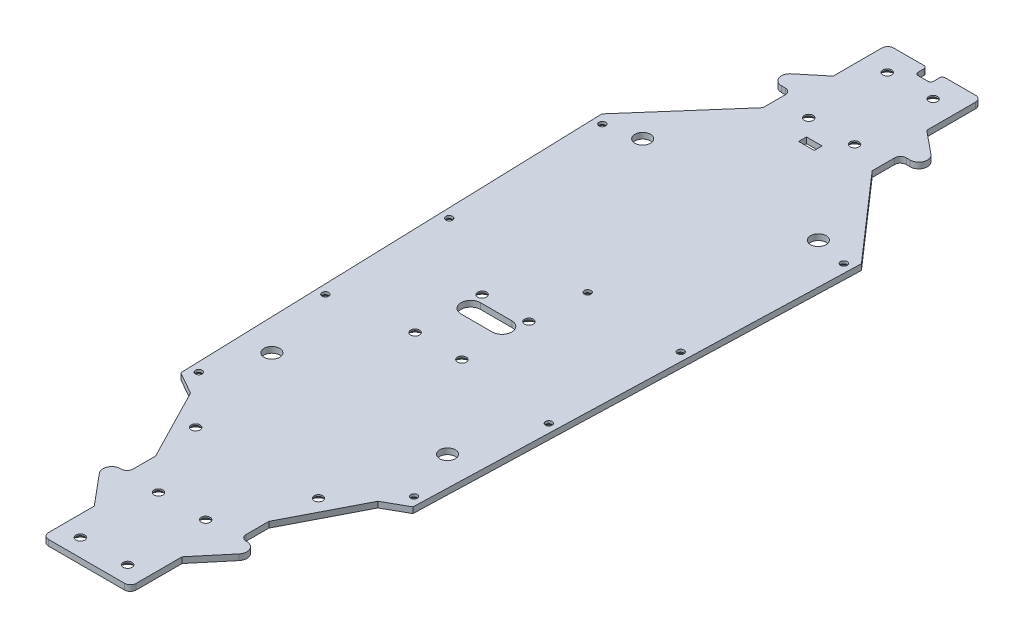
SolidWorks part; units mm, degrees
material "1060-H12"
ref_plane "Plano frontal" through (0, 0, 0) normal (0, 0, 1) x (1, 0, 0)
ref_plane "Plano superior" through (0, 0, 0) normal (0, 1, 0) x (1, 0, 0)
ref_plane "Plano direito" through (0, 0, 0) normal (1, 0, 0) x (0, 0, -1)
sketch "Esboço1" plane through (0, 0, 0) normal (0, 1, 0) x (1, 0, 0)
  line L0 (0, -26.4872) -> (0, 31.5227) construction
  line L1 (-2.5, 209.375) -> (2.5, 209.375)
  line L2 (4, 210.875) -> (4, 213.875)
  line L3 (5.5, 215.375) -> (21, 215.375)
  line L4 (24, 212.375) -> (24, 187.375)
  line L5 (24, 187.375) -> (35.8087, 177.675)
  line L6 (33.0159, 169.875) -> (31, 169.875)
  line L7 (28, 166.875) -> (28, 155.375)
  line L8 (-66.5, 111.375) -> (-28, 155.375)
  line L9 (66.5, 111.375) -> (59.5, -111.375)
  line L10 (59.5, -111.375) -> (48, -117.875)
  line L11 (48, -117.875) -> (29, -154.7701)
  line L12 (29, -154.7701) -> (29, -166.3701)
  line L13 (35.824, -176.7566) -> (22.5, -192.692)
  line L14 (32, -169.3701) -> (32.3717, -169.3701)
  line L15 (22.5, -192.692) -> (22.5, -216.192)
  line L16 (66.5, 111.375) -> (28, 155.375)
  line L17 (19.5, -219.192) -> (-19.5, -219.192)
  line L18 (-22.5, -192.692) -> (-22.5, -216.192)
  line L19 (-32, -169.3701) -> (-32.3717, -169.3701)
  line L20 (-35.824, -176.7566) -> (-22.5, -192.692)
  line L21 (-29, -154.7701) -> (-29, -166.3701)
  line L22 (-48, -117.875) -> (-29, -154.7701)
  line L23 (-59.5, -111.375) -> (-48, -117.875)
  line L24 (-66.5, 111.375) -> (-59.5, -111.375)
  line L25 (-63, 0) -> (0, 0) construction
  line L27 (-28, 166.875) -> (-28, 155.375)
  line L28 (-33.0159, 169.875) -> (-31, 169.875)
  line L29 (-24, 187.375) -> (-35.8087, 177.675)
  line L30 (-24, 212.375) -> (-24, 187.375)
  line L31 (-5.5, 215.375) -> (-21, 215.375)
  line L32 (-4, 210.875) -> (-4, 213.875)
  arc A0 (-5.5, 215.375) -> (-4, 213.875) centre (-5.5, 213.875) cw
  arc A1 (-4, 210.875) -> (-2.5, 209.375) centre (-2.5, 210.875) ccw
  arc A2 (4, 210.875) -> (2.5, 209.375) centre (2.5, 210.875) cw
  arc A3 (5.5, 215.375) -> (4, 213.875) centre (5.5, 213.875) ccw
  arc A4 (22.5, -216.192) -> (19.5, -219.192) centre (19.5, -216.192) cw
  arc A5 (24, 212.375) -> (21, 215.375) centre (21, 212.375) ccw
  arc A6 (-32, -169.3701) -> (-29, -166.3701) centre (-32, -166.3701) ccw
  arc A7 (-32.3717, -169.3701) -> (-35.824, -176.7566) centre (-32.3717, -173.8701) ccw
  arc A8 (-31, 169.875) -> (-28, 166.875) centre (-31, 166.875) cw
  arc A9 (-35.8087, 177.675) -> (-33.0159, 169.875) centre (-33.0159, 174.275) ccw
  arc A10 (-24, 212.375) -> (-21, 215.375) centre (-21, 212.375) cw
  arc A11 (-22.5, -216.192) -> (-19.5, -219.192) centre (-19.5, -216.192) ccw
  arc A12 (35.8087, 177.675) -> (33.0159, 169.875) centre (33.0159, 174.275) cw
  arc A13 (31, 169.875) -> (28, 166.875) centre (31, 166.875) ccw
  arc A14 (32.3717, -169.3701) -> (35.824, -176.7566) centre (32.3717, -173.8701) cw
  arc A15 (32, -169.3701) -> (29, -166.3701) centre (32, -166.3701) cw
  point P4 (22.5, -434.567)
  point P14 (-4, 215.375)
  point P18 (-4, 209.375)
  point P22 (0, 209.375)
  point P27 (4, 209.375)
  point P28 (4, 215.375)
  point P57 (0, -219.192)
  point P72 (-22.5, -434.567)
  point P80 (0, -219.192)
  dimension "D24" = 1.5
  dimension "D25" = 4.4
  dimension "D26" = 3
  dimension "D27" = 9.7
  dimension "D22" = 4.5
  dimension "D3" = 4
  dimension "D4" = 6
  dimension "D5" = 28
  dimension "D6" = 60
  dimension "D7" = 28
  dimension "D8" = 14.5
  dimension "D9" = 24
  dimension "D10" = 59.5
  dimension "D11" = 66.5
  dimension "D12" = 222.75
  dimension "D13" = 22.5
  dimension "D14" = 44
  dimension "D15" = 48
  dimension "D16" = 26.5
  dimension "D17" = 14.6
  dimension "D18" = 6.5
  dimension "D19" = 29
  dimension "D20" = 43.3951
  dimension "D21" = 64.4219
  dimension "D23" = 15.9354
extrude "Ressalto-extrusão1" add sketch "Esboço1" along normal blind 3
sketch "Esboço2" plane through (0, 3, 0) normal (0, 1, 0) x (1, 0, 0)
  line L0 (0, -203.2012) -> (0, 0) construction
  line L2 (-19.5, -219.192) -> (19.5, -219.192) construction
  circle A0 centre (-45, -79.192) radius 4
  circle A1 centre (45, -79.192) radius 4
  circle A2 centre (45, 110.808) radius 4
  circle A3 centre (-45, 110.808) radius 4
  dimension "D1" = 8
  dimension "D2" = 190
  dimension "D3" = 45
  dimension "D4" = 140
extrude "Corte-extrusão1" cut sketch "Esboço2" against normal blind 10
hole_wizard "Escareado para SFHCS M31" positions "Esboço5" profile "Esboço6" countersink size "M3" standard "Ansi Metric" end condition through all
sketch "Esboço5" plane through (0, 0, 0) normal (0, -1, 0) x (-1, 0, 0)
  point P0 (-55.1512, -106.4919)
  point P3 (55.1512, -106.4919)
  point P6 (57.2557, -39.525)
  point P9 (-57.2557, -39.525)
  point P12 (-59.3141, 25.975)
  point P15 (59.3141, 25.975)
  point P18 (-61.8595, 106.975)
  point P21 (61.8595, 106.975)
  point P25 (-9.0709, 28.5741)
sketch "Esboço6" plane through (55.1512, 0, 106.4919) normal (1, 0, 0) x (0, 0, -1)
  line L0 (0, 0) -> (0, 3)
  line L1 (0, 3) -> (1.7, 3)
  line L2 (1.7, 3) -> (1.7, 1.66)
  line L3 (1.7, 1.66) -> (3.36, 0)
  line L5 (3.36, 0) -> (0, 0)
  line L6 (-1.7, 1.66) -> (-3.36, 0) construction
  line L11 (0, -6.35) -> (0, 107.95) construction
  dimension "Thru Hole Dia." = 3.4
  dimension "Thru Hole Depth" = 3
  dimension "Near C'Sink Dia." = 6.72
  dimension "Near C'Sink Angle" = 90
hole_wizard "Escareado para SFHCS M41" positions "Esboço7" profile "Esboço8" countersink size "M4" standard "Ansi Metric" end condition through all
sketch "Esboço7" plane through (0, 0, 0) normal (0, -1, 0) x (-1, 0, 0)
  point P0 (-12.1, -170.192)
  point P3 (-12.1, -210.192)
  point P6 (12.1, -210.192)
  point P9 (12.1, -170.192)
  point P12 (31.4522, -131.7701)
  point P15 (-31.4522, -131.7701)
  point P18 (-6.6745, -33.492)
  point P21 (17.3255, -33.492)
  point P24 (16.9933, 0.508)
  point P27 (-7.0067, 0.508)
  point P30 (-11.75, 162.6241)
  point P33 (11.75, 162.6241)
  point P36 (11.75, 202.8741)
  point P39 (-11.75, 202.8741)
sketch "Esboço8" plane through (12.1, 0, 170.192) normal (1, 0, 0) x (0, 0, -1)
  line L0 (0, 0) -> (0, 3)
  line L1 (0, 3) -> (2.25, 3)
  line L2 (2.25, 3) -> (2.25, 2.23)
  line L3 (2.25, 2.23) -> (4.48, 0)
  line L5 (4.48, 0) -> (0, 0)
  line L6 (-2.25, 2.23) -> (-4.48, 0) construction
  line L11 (0, -6.35) -> (0, 107.95) construction
  dimension "Thru Hole Dia." = 4.5
  dimension "Thru Hole Depth" = 3
  dimension "Near C'Sink Dia." = 8.96
  dimension "Near C'Sink Angle" = 90
sketch "Esboço9" plane through (0, 0, 0) normal (0, -1, 0) x (1, 0, 0)
  line L0 (-13.7943, 8.492) -> (2.2057, 8.492) construction
  line L1 (-13.7943, 13.492) -> (2.2057, 13.492)
  line L2 (-13.7943, 3.492) -> (2.2057, 3.492)
  line L4 (4.15, -153.5741) -> (-3.85, -153.5741)
  line L5 (4.15, -153.5741) -> (4.15, -149.5741)
  line L6 (4.15, -149.5741) -> (-3.85, -149.5741)
  line L7 (-3.85, -153.5741) -> (-3.85, -149.5741)
  arc A0 (-13.7943, 13.492) -> (-13.7943, 3.492) centre (-13.7943, 8.492) ccw
  arc A1 (2.2057, 3.492) -> (2.2057, 13.492) centre (2.2057, 8.492) ccw
  point P2 (-5.7943, 8.492)
extrude "Corte-extrusão2" cut sketch "Esboço9" against normal through all
